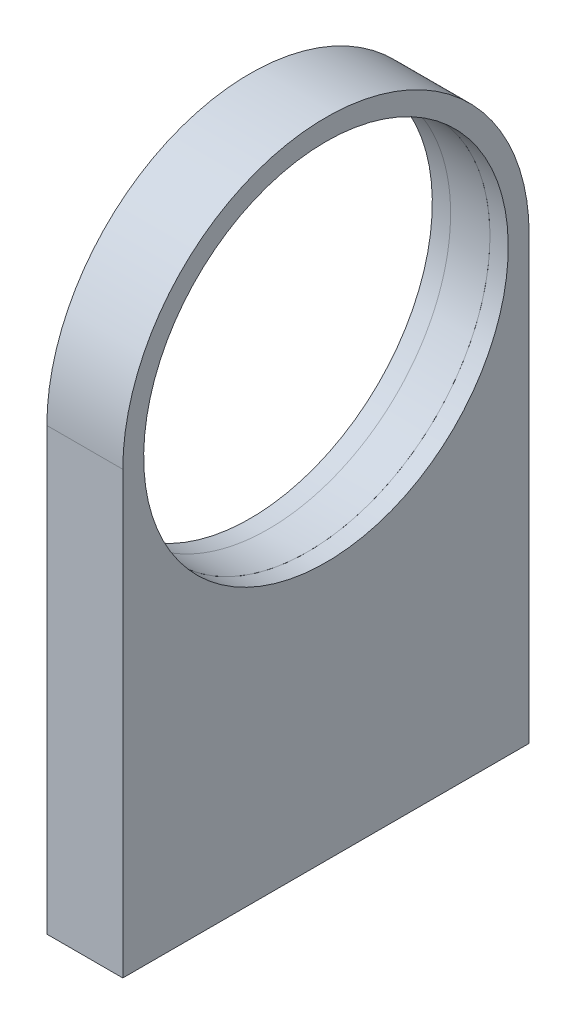
SolidWorks part; units mm, degrees
ref_plane "Płaszczyzna przednia" through (0, 0, 0) normal (0, 0, 1) x (1, 0, 0)
ref_plane "Płaszczyzna górna" through (0, 0, 0) normal (0, 1, 0) x (1, 0, 0)
ref_plane "Płaszczyzna prawa" through (0, 0, 0) normal (1, 0, 0) x (0, 0, -1)
sketch "Szkic1" plane through (0, 0, 0) normal (0, 0, 1) x (1, 0, 0)
  line L0 (0, 0) -> (-72.7399, 0) construction
  line L1 (-72.7399, 0) -> (-72.7399, 77.0207) construction
  line L2 (-52.7399, 77.0207) -> (-92.7399, 77.0207)
  line L3 (-92.7399, 77.0207) -> (-92.7399, 88.0207)
  line L4 (-92.7399, 88.0207) -> (-83.1109, 88.0207)
  line L5 (-83.1109, 88.0207) -> (-83.1109, 96.0207)
  line L6 (-83.1109, 96.0207) -> (-92.7399, 96.0207)
  line L7 (-92.7399, 96.0207) -> (-92.7399, 107.0207)
  line L8 (-92.7399, 107.0207) -> (-52.7399, 107.0207)
  line L9 (-52.7399, 77.0207) -> (-52.7399, 88.0207)
  line L10 (-52.7399, 88.0207) -> (-62.3688, 88.0207)
  line L11 (-62.3688, 88.0207) -> (-62.3688, 96.0207)
  line L12 (-62.3688, 96.0207) -> (-52.7399, 96.0207)
  line L13 (-52.7399, 96.0207) -> (-52.7399, 107.0207)
  point P17 (-72.7399, 107.0207)
  dimension "D1" = 20
  dimension "D2" = 30
  dimension "D3" = 11
revolve "Obrót1" add sketch "Szkic1" angle 360 about L0
ref_plane "Płaszczyzna1" through (-92.7399, 0, 0) normal (-1, 0, 0) x (0, 0, 1)
sketch "Szkic2" plane through (-92.7399, 0, 0) normal (-1, 0, 0) x (0, 0, 1)
  line L0 (0, 0) -> (-51.2114, 0) construction
  line L1 (-107.0207, 0) -> (-107.0207, -232.0579)
  line L2 (-35.7025, -3.4162) -> (-35.7025, -5.4814)
  line L3 (-107.0207, -232.0579) -> (107.0207, -232.0579)
  line L4 (107.0207, -232.0579) -> (107.0207, 0)
  circle A0 centre (0, 0) radius 107.0207 construction
  arc A1 (-107.0207, 0) -> (107.0207, 0) centre (0, 0) ccw
extrude "Dodanie-wyciągnięcie1" add sketch "Szkic2" against normal blind 40 contours A1 L1 L3 L4
sketch "Szkic3" plane through (-92.7399, 0, 0) normal (-1, 0, 0) x (0, 0, 1)
  circle A0 centre (0, 0) radius 96
sketch "Szkic4" plane through (-92.7399, 0, 0) normal (-1, 0, 0) x (0, 0, 1)
  circle A0 centre (0, 0) radius 96
  circle A1 centre (0, 0) radius 77.0207
extrude "Wytnij-wyciągnięcie1" cut sketch "Szkic4" against normal blind 40 contours A0
